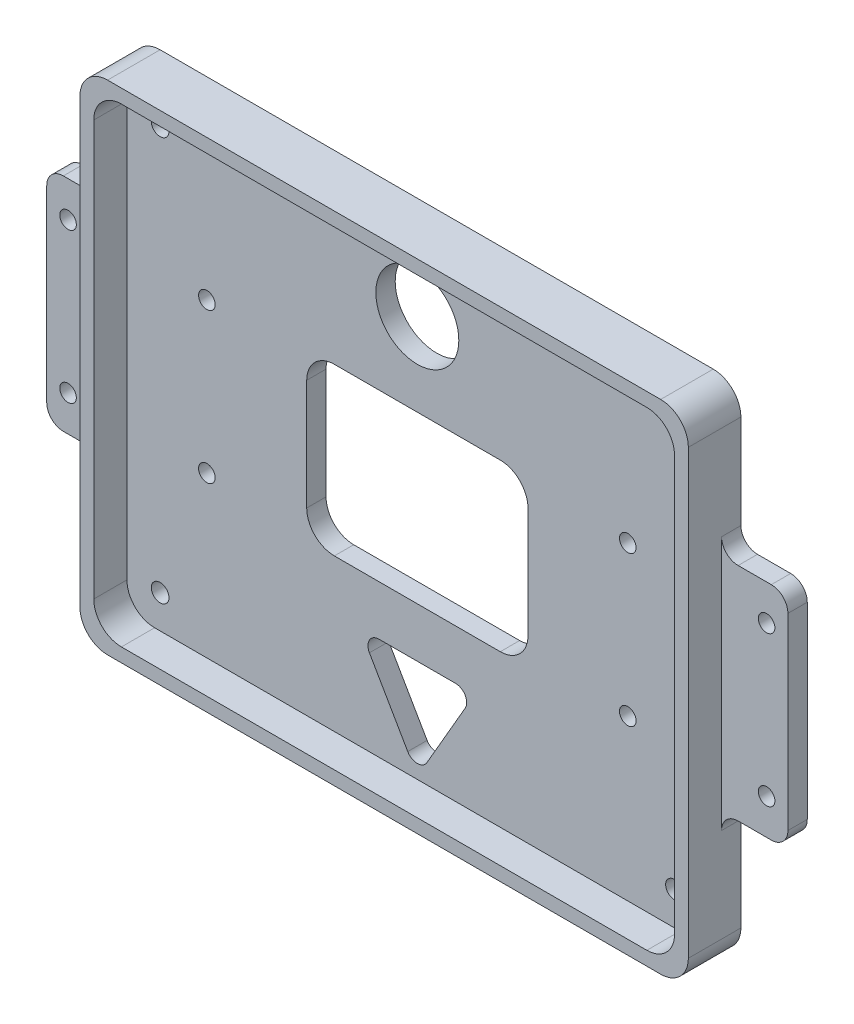
SolidWorks part; units mm, degrees
ref_plane "Front Plane" through (0, 0, 0) normal (0, 0, 1) x (1, 0, 0)
ref_plane "Top Plane" through (0, 0, 0) normal (0, 1, 0) x (1, 0, 0)
ref_plane "Right Plane" through (0, 0, 0) normal (1, 0, 0) x (0, 0, -1)
sketch "Sketch1" plane through (0, 0, 0) normal (0, 0, 1) x (1, 0, 0)
  line L0 (0, 0) -> (46.5, 0) construction
  line L1 (50, -45) -> (-50, -45)
  line L2 (55, -40) -> (55, 40)
  line L3 (50, 45) -> (-50, 45)
  line L4 (-55, -40) -> (-55, 40)
  line L5 (55, -45) -> (-55, 45) construction
  line L6 (55, 45) -> (-55, -45) construction
  line L7 (0, 0) -> (-46.5, 0) construction
  line L8 (-46.5, 0) -> (-46.5, 36.5) construction
  line L9 (46.5, 0) -> (46.5, 36.5) construction
  line L10 (0, 0) -> (0, 13.55) construction
  line L11 (0, 13.55) -> (38.05, 13.55) construction
  line L12 (38.05, 13.55) -> (38.05, -13.55) construction
  circle A0 centre (-46.5, 36.5) radius 1.6
  circle A1 centre (46.5, 36.5) radius 1.6
  circle A2 centre (46.5, -36.5) radius 1.6
  circle A3 centre (-46.5, -36.5) radius 1.6
  arc A4 (55, 40) -> (50, 45) centre (50, 40) ccw
  arc A5 (55, -40) -> (50, -45) centre (50, -40) cw
  arc A6 (-50, -45) -> (-55, -40) centre (-50, -40) cw
  arc A7 (-55, 40) -> (-50, 45) centre (-50, 40) cw
  circle A8 centre (38.05, 13.55) radius 1.5
  circle A9 centre (38.05, -13.55) radius 1.5
  circle A10 centre (-38.05, -13.55) radius 1.5
  circle A11 centre (-38.05, 13.55) radius 1.5
  point P0 (0, 0)
  dimension "D6" = 3.2
  dimension "D7" = 3.2
  dimension "D8" = 5
  dimension "D11" = 3
  dimension "D13" = 3
  dimension "D1" = 110
  dimension "D2" = 90
  dimension "D3" = 46.5
  dimension "D4" = 46.5
  dimension "D5" = 36.5
  dimension "D9" = 13.55
  dimension "D10" = 38.05
  dimension "D12" = 27.1
extrude "Boss-Extrude1" add sketch "Sketch1" along normal blind 3.5
ref_plane "Plane1" through (0, 0, 0) normal (0, 0, -1) x (-1, 0, 0)
sketch "Sketch2" plane through (0, 0, 0) normal (0, 0, -1) x (-1, 0, 0)
  line L0 (0, 0) -> (0, 30) construction
  line L1 (-15, -15) -> (15, -15)
  line L2 (-20, -10) -> (-20, 10)
  line L3 (-15, 15) -> (15, 15)
  line L4 (20, -10) -> (20, 10)
  line L5 (-20, -15) -> (20, 15) construction
  line L6 (-20, 15) -> (20, -15) construction
  line L7 (0, 0) -> (0, -30) construction
  line L9 (1.7321, -39) -> (8.6603, -27)
  line L10 (6.9282, -24) -> (-6.9282, -24)
  line L11 (-8.6603, -27) -> (-1.7321, -39)
  arc A0 (20, 10) -> (15, 15) centre (15, 10) ccw
  arc A1 (20, -10) -> (15, -15) centre (15, -10) cw
  arc A2 (-15, -15) -> (-20, -10) centre (-15, -10) cw
  arc A3 (-20, 10) -> (-15, 15) centre (-15, 10) cw
  circle A4 centre (0, 30) radius 7.5
  circle A5 centre (0, -30) radius 6 construction
  arc A6 (1.7321, -39) -> (-1.7321, -39) centre (0, -38) cw
  arc A7 (8.6603, -27) -> (6.9282, -24) centre (6.9282, -26) ccw
  arc A8 (-8.6603, -27) -> (-6.9282, -24) centre (-6.9282, -26) cw
  point P0 (0, 0)
  dimension "D3" = 5
  dimension "D5" = 15
  dimension "D7" = 12
  dimension "D8" = 2
  dimension "D1" = 40
  dimension "D2" = 30
  dimension "D4" = 30
  dimension "D6" = 30
extrude "Cut-Extrude1" cut sketch "Sketch2" against normal blind 10
ref_plane "Plane2" through (0, 0, 3.5) normal (0, 0, 1) x (1, 0, 0)
sketch "Sketch3" plane through (0, 0, 3.5) normal (0, 0, 1) x (1, 0, 0)
  line L1 (50, -45) -> (-50, -45)
  line L2 (55, -40) -> (55, 40)
  line L3 (50, 45) -> (-50, 45)
  line L4 (-55, -40) -> (-55, 40)
  line L5 (55, -45) -> (-55, 45) construction
  line L6 (55, 45) -> (-55, -45) construction
  arc A0 (55, 40) -> (50, 45) centre (50, 40) ccw
  arc A1 (50, -45) -> (55, -40) centre (50, -40) ccw
  arc A2 (-50, -45) -> (-55, -40) centre (-50, -40) cw
  arc A3 (-50, 45) -> (-55, 40) centre (-50, 40) ccw
  point P0 (0, 0)
  dimension "D1" = 5
extrude "Boss-Extrude2" add sketch "Sketch3" along normal blind 6
ref_plane "Plane3" through (0, 0, 9.5) normal (0, 0, 1) x (1, 0, 0)
sketch "Sketch4" plane through (0, 0, 9.5) normal (0, 0, 1) x (1, 0, 0)
  line L1 (47.5, -42.5) -> (-47.5, -42.5)
  line L2 (52.5, -37.5) -> (52.5, 37.5)
  line L3 (47.5, 42.5) -> (-47.5, 42.5)
  line L4 (-52.5, -37.5) -> (-52.5, 37.5)
  line L5 (52.5, -42.5) -> (-52.5, 42.5) construction
  line L6 (52.5, 42.5) -> (-52.5, -42.5) construction
  arc A0 (-47.5, -42.5) -> (-52.5, -37.5) centre (-47.5, -37.5) cw
  arc A1 (47.5, -42.5) -> (52.5, -37.5) centre (47.5, -37.5) ccw
  arc A2 (52.5, 37.5) -> (47.5, 42.5) centre (47.5, 37.5) ccw
  arc A3 (-52.5, 37.5) -> (-47.5, 42.5) centre (-47.5, 37.5) cw
  point P0 (0, 0)
  dimension "D3" = 5
  dimension "D1" = 105
  dimension "D2" = 85
extrude "Cut-Extrude2" cut sketch "Sketch4" against normal blind 6
ref_plane "Plane4" through (0, 0, 0) normal (0, 0, -1) x (-1, 0, 0)
sketch "Sketch5" plane through (0, 0, 0) normal (0, 0, -1) x (-1, 0, 0)
  line L0 (-38.05, 13.55) -> (-38.05, -13.55) construction
  line L1 (-38.05, 13.55) -> (-63.15, 13.55) construction
  line L2 (-55, 0) -> (-55, 20) construction
  line L3 (-55, -40) -> (-55, 40) construction
  line L4 (-55, 20) -> (-64, 20)
  line L5 (-67, 17) -> (-67, -17)
  line L6 (-64, -20) -> (-55, -20)
  line L7 (-55, -20) -> (-55, 20)
  line L8 (-38.05, -13.55) -> (-63.15, -13.55) construction
  line L9 (0, 0) -> (0, 10.981) construction
  line L10 (64, -20) -> (55, -20)
  line L11 (67, 17) -> (67, -17)
  line L12 (55, 20) -> (64, 20)
  line L13 (55, -20) -> (55, 20)
  circle A0 centre (-63.15, 13.55) radius 1.5
  arc A1 (-64, -20) -> (-67, -17) centre (-64, -17) cw
  arc A2 (-67, 17) -> (-64, 20) centre (-64, 17) cw
  circle A3 centre (-63.15, -13.55) radius 1.5
  circle A4 centre (63.15, -13.55) radius 1.5
  circle A5 centre (63.15, 13.55) radius 1.5
  arc A6 (64, -20) -> (67, -17) centre (64, -17) ccw
  arc A7 (67, 17) -> (64, 20) centre (64, 17) ccw
  point P15 (-67, -20)
  point P18 (-67, 20)
  dimension "D2" = 3
  dimension "D6" = 3
  dimension "D7" = 3
  dimension "D1" = 25.1
  dimension "D3" = 20
  dimension "D4" = 12
  dimension "D5" = 40
extrude "Boss-Extrude3" add sketch "Sketch5" against normal blind 3.5
fillet "Fillet1" radius 3 4 edges at (55, -20, 1.75) (55, 20, 1.75) (-55, 20, 1.75) (-55, -20, 1.75)
